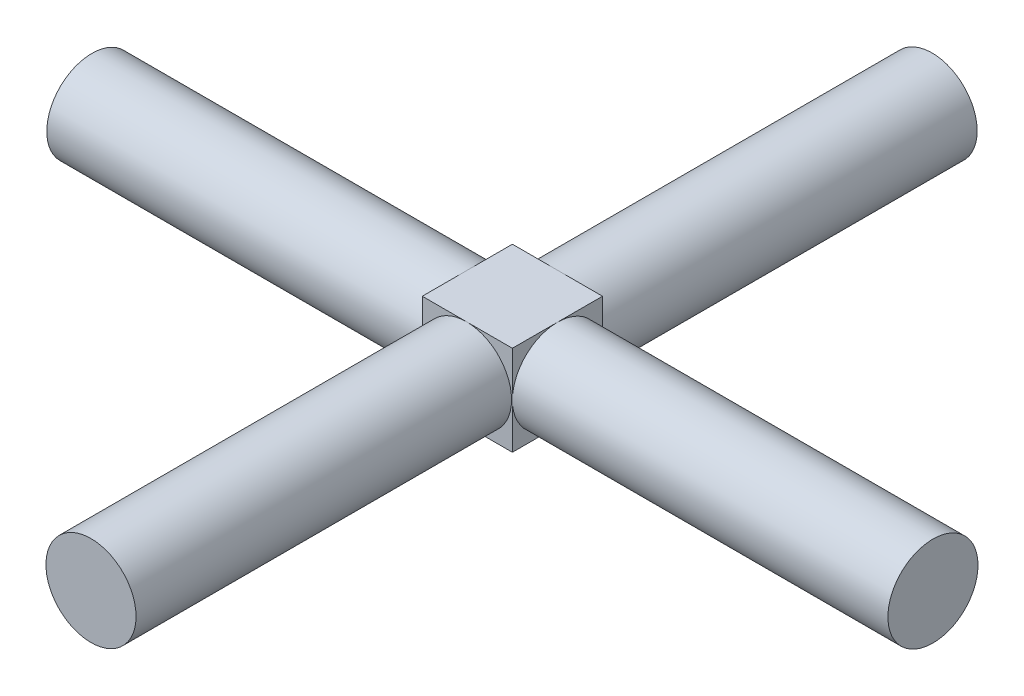
SolidWorks part; units mm, degrees
ref_plane "Front Plane" through (0, 0, 0) normal (0, 0, 1) x (1, 0, 0)
ref_plane "Top Plane" through (0, 0, 0) normal (0, 1, 0) x (1, 0, 0)
ref_plane "Right Plane" through (0, 0, 0) normal (1, 0, 0) x (0, 0, -1)
sketch "Sketch1" plane through (0, 0, 0) normal (0, 1, 0) x (1, 0, 0)
  line L1 (-0.75, -0.75) -> (0.75, -0.75)
  line L2 (-0.75, -0.75) -> (-0.75, 0.75)
  line L3 (-0.75, 0.75) -> (0.75, 0.75)
  line L4 (0.75, -0.75) -> (0.75, 0.75)
  line L5 (-0.75, -0.75) -> (0.75, 0.75) construction
  line L6 (-0.75, 0.75) -> (0.75, -0.75) construction
  point P0 (0, 0)
  dimension "D1" = 1.5
  dimension "D2" = 1.5
extrude "Boss-Extrude1" add sketch "Sketch1" along normal blind 1.5
sketch "Sketch3" plane through (0, 0, 0) normal (1, 0, 0) x (0, 0, -1)
  line L0 (-0.75, 0) -> (0.75, 0) construction
  circle A0 centre (0, 0.75) radius 0.75
  dimension "D2" = 1.5
  dimension "D1" = 0.75
extrude "Boss-Extrude2" add sketch "Sketch3" along normal mid plane 14
sketch "Sketch4" plane through (0, 0, 0) normal (0, 0, 1) x (1, 0, 0)
  line L0 (-0.75, 0) -> (0.75, 0) construction
  circle A0 centre (-0.014, 0.75) radius 0.75
  dimension "D2" = 1.5
  dimension "D1" = 0.75
extrude "Boss-Extrude3" add sketch "Sketch4" along normal mid plane 14
